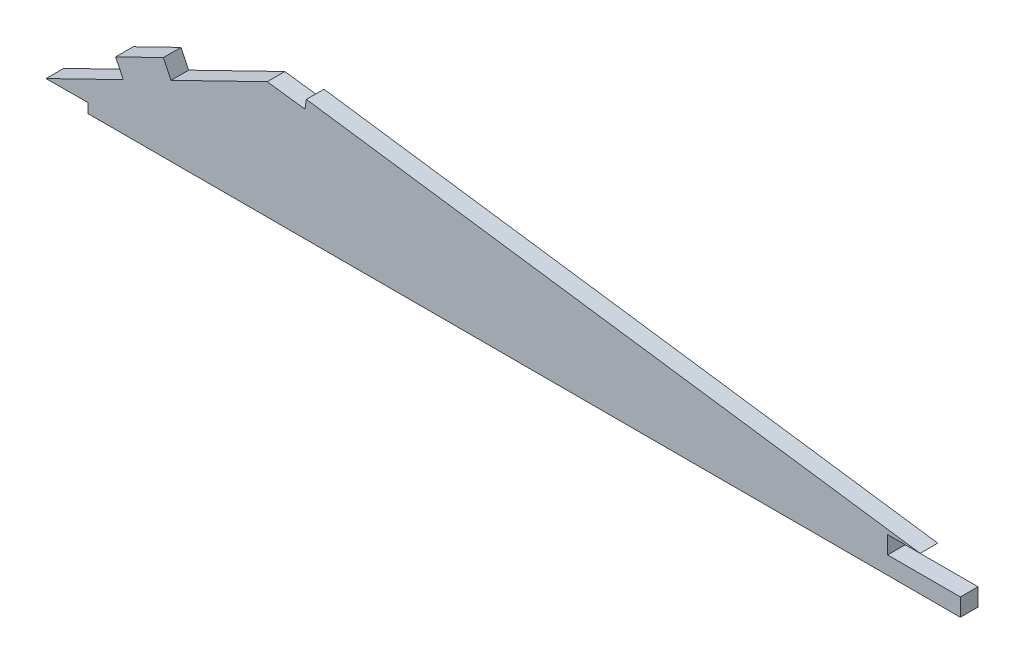
SolidWorks part; units mm, degrees
ref_plane "前视基准面" through (0, 0, 0) normal (0, 0, 1) x (1, 0, 0)
ref_plane "上视基准面" through (0, 0, 0) normal (0, 1, 0) x (1, 0, 0)
ref_plane "右视基准面" through (0, 0, 0) normal (1, 0, 0) x (0, 0, -1)
sketch "Model" plane through (0, 0, 0) normal (0, 0, 1) x (1, 0, 0)
  line L0 (16.7213, 12.8223) -> (27.6289, 18.1423)
  line L1 (11.3026, 10.1795) -> (10.4259, 11.977)
  line L2 (10.4259, 11.977) -> (15.8445, 14.6199)
  line L3 (15.8445, 14.6199) -> (16.7213, 12.8223)
  line L4 (2.529, 5.9003) -> (11.3026, 10.1795)
  line L5 (7.3146, 4.8356) -> (106.2916, 4.8356)
  line L6 (32.0713, 18.6245) -> (101.7229, 8.8356)
  line L7 (27.6289, 18.1423) -> (31.9231, 17.5868)
  line L8 (31.9231, 17.5868) -> (32.0713, 18.6245)
  line L9 (7.3146, 4.8356) -> (7.3104, 5.9188)
  line L10 (7.3104, 5.9188) -> (2.529, 5.9003)
  line L11 (98.0354, 6.8356) -> (106.2916, 6.8356)
  line L12 (98.0354, 8.8356) -> (101.7229, 8.8356)
  line L13 (98.0354, 6.8356) -> (98.0354, 8.8356)
  line L14 (106.2916, 4.8356) -> (106.2916, 6.8356)
extrude "凸台-拉伸1" add sketch "Model" along normal blind 2
